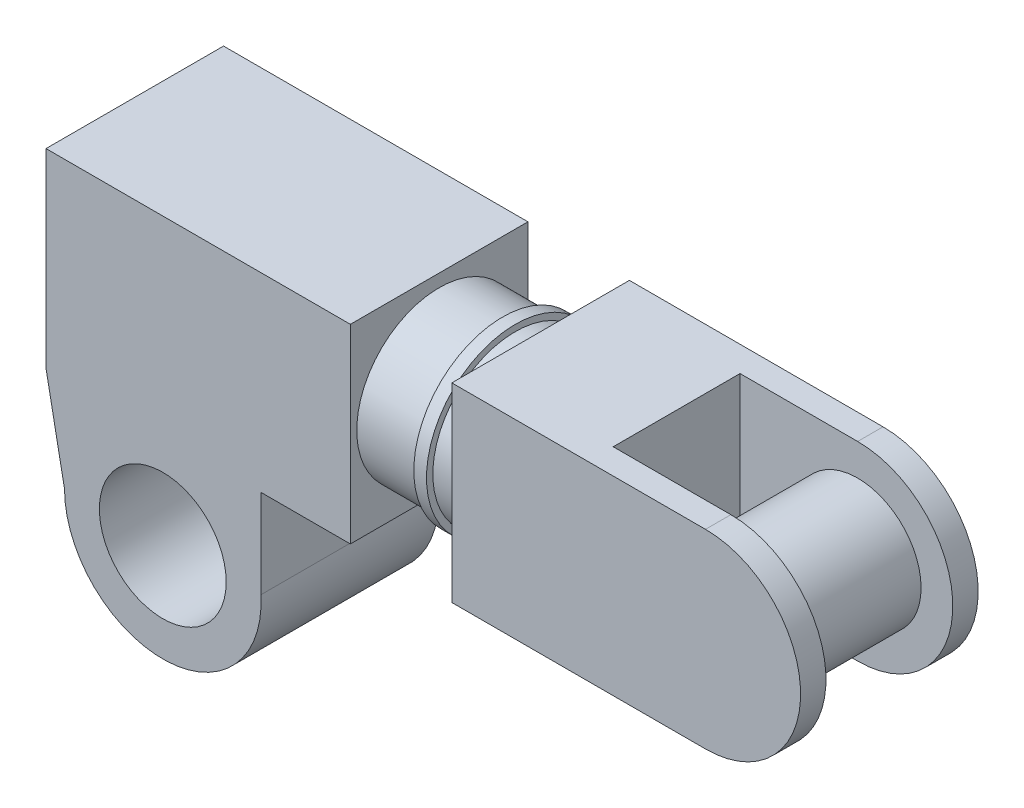
SolidWorks part; units mm, degrees
ref_plane "Front Plane" through (0, 0, 0) normal (0, 0, 1) x (1, 0, 0)
ref_plane "Top Plane" through (0, 0, 0) normal (0, 1, 0) x (1, 0, 0)
ref_plane "Right Plane" through (0, 0, 0) normal (1, 0, 0) x (0, 0, -1)
sketch "Sketch1" plane through (0, 0, 0) normal (1, 0, 0) x (0, 0, -1)
  line L1 (700, 750) -> (-700, 750)
  line L2 (700, 750) -> (700, -750)
  line L3 (700, -750) -> (-700, -750)
  line L4 (-700, 750) -> (-700, -750)
  line L5 (700, 750) -> (-700, -750) construction
  line L6 (700, -750) -> (-700, 750) construction
  point P0 (0, 0)
  dimension "D1" = 1500
  dimension "D2" = 1400
extrude "Boss-Extrude1" add sketch "Sketch1" along normal blind 2400
sketch "Sketch2" plane through (2400, 0, 0) normal (1, 0, 0) x (0, 0, -1)
  circle A0 centre (0, 0) radius 650
  dimension "D1" = 1300
extrude "Boss-Extrude2" add sketch "Sketch2" along normal blind 500
sketch "Sketch3" plane through (2900, 0, 0) normal (1, 0, 0) x (0, 0, -1)
  circle A0 centre (0, 0) radius 700
  dimension "D1" = 1400
extrude "Boss-Extrude3" add sketch "Sketch3" along normal blind 100
sketch "Sketch4" plane through (0, 0, 700) normal (0, 0, 1) x (1, 0, 0)
  line L0 (0, -750) -> (145.7852, -1500)
  line L1 (0, 750) -> (0, -750) construction
  line L2 (1695.7852, -750) -> (1694.1706, -1450)
  line L3 (2400, -750) -> (0, -750) construction
  circle A0 centre (920.7852, -1500) radius 500
  arc A1 (145.7852, -1500) -> (1694.1706, -1450) centre (920.7852, -1500) ccw
  line M5 (0, -750) -> (2400, -750)
  dimension "D1" = 1550
  dimension "D2" = 1000
  dimension "D3" = 750
  dimension "D4" = 191
  dimension "D5" = 700
  dimension "D6" = 11.132
extrude "Boss-Extrude4" add sketch "Sketch4" against normal blind 1400 contours L0 A1 L2 A0 M5
sketch "Sketch5" plane through (3000, 0, 0) normal (1, 0, 0) x (0, 0, -1)
  circle A0 centre (0, 0) radius 650
  dimension "D1" = 1300
extrude "Boss-Extrude5" add sketch "Sketch5" along normal blind 200
sketch "Sketch6" plane through (0, 0, 0) normal (0, 0, 1) x (1, 0, 0)
  line L0 (5200, 750) -> (3200, 750)
  line L1 (3200, 750) -> (3200, -750)
  line L2 (3200, -750) -> (5200, -750)
  line L3 (3200, -650) -> (3200, 650) construction
  arc A0 (5200, -750) -> (5200, 750) centre (5200, 0) ccw
  dimension "D1" = 1500
  dimension "D2" = 2000
extrude "Boss-Extrude7" add sketch "Sketch6" along normal mid plane 1400
sketch "Sketch7" plane through (0, 0, 0) normal (0, 0, 1) x (1, 0, 0)
  line L0 (5200, 750) -> (4272.3765, 750)
  line L1 (5200, -750) -> (4272.3765, -750)
  line L2 (4272.3765, 750) -> (4272.3765, -750)
  arc A0 (5200, -750) -> (5200, 750) centre (5200, 0) ccw construction
  arc A1 (5200, -750) -> (5200, 750) centre (5200, 0) ccw
extrude "Cut-Extrude1" cut sketch "Sketch7" against normal mid plane 1000
sketch "Sketch8" plane through (0, 0, 700) normal (0, 0, 1) x (1, 0, 0)
  circle A0 centre (5200, 0) radius 500
  arc A3 (5200, -750) -> (5200, 750) centre (5200, 0) ccw construction
  point P2 (0, 0)
  point P5 (0, 0)
  dimension "D1" = 1000
  dimension "D2" = 0
extrude "Boss-Extrude8" add sketch "Sketch8" against normal through all
